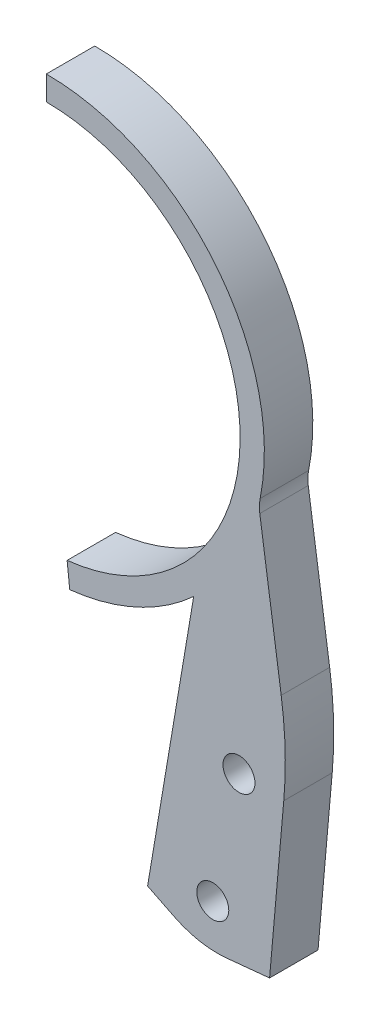
SolidWorks part; units mm, degrees
ref_plane "前视基准面" through (0, 0, 0) normal (0, 0, 1) x (1, 0, 0)
ref_plane "上视基准面" through (0, 0, 0) normal (0, 1, 0) x (1, 0, 0)
ref_plane "右视基准面" through (0, 0, 0) normal (1, 0, 0) x (0, 0, -1)
other "Configuration Table"
sketch "草图1" plane through (0, 0, 0) normal (0, 0, 1) x (1, 0, 0)
  line L5 (0, 0) -> (-23, 0) construction
  line L6 (-11.5, 0) -> (-11.5, 74.1629) construction
  line L9 (-11.5, 79.5) -> (-11.5, 82)
  line L11 (-1.0471, 14.6646) -> (3.7097, 42.9194)
  line L12 (-1.6292, 12.8088) -> (6.0667, 37.3455) construction
  line L13 (-1.0471, 14.6646) -> (4.2787, 12.0253)
  line L14 (4.2787, 12.0253) -> (11.5399, 12.741)
  line L15 (14.2578, 35.2287) -> (10.6514, 5.3898) construction
  line L16 (11.5399, 12.741) -> (13.4146, 33.9693)
  line L17 (13.4146, 33.9693) -> (10.427, 54.4544)
  line L18 (-9.3493, 39.616) -> (-9.0804, 37.1305)
  circle A0 centre (5.6795, 16.6838) radius 1.65 construction
  circle A1 centre (8.3823, 29.3997) radius 1.65 construction
  circle A3 centre (5.6795, 16.6838) radius 1.65
  circle A4 centre (8.3823, 29.3997) radius 1.65
  arc A8 (-9.3493, 39.616) -> (-11.5, 79.5) centre (-11.5, 59.5) ccw
  arc A9 (-9.0804, 37.1305) -> (3.7097, 42.9194) centre (-11.5, 59.5) ccw
  arc A10 (10.427, 54.4544) -> (-11.5, 82) centre (-11.5, 59.5) ccw
  dimension "D1" = 22.5
  dimension "D2" = 59.5
extrude "凸台-拉伸1" add sketch "草图1" along normal blind 5
fillet "圆角2" radius 4 1 edges at (10.427, 54.4544, 2.5)
fillet "圆角3" radius 40 1 edges at (13.4146, 33.9693, 2.5)
fillet "圆角4" radius 10 1 edges at (4.2787, 12.0253, 2.5)
